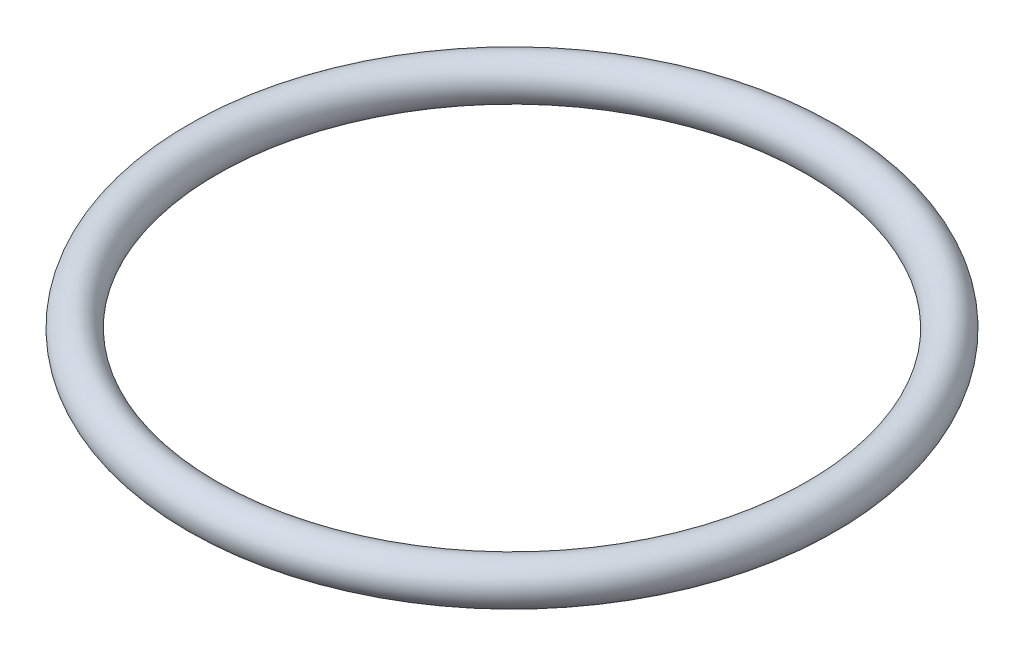
SolidWorks part; units mm, degrees
ref_plane "正面" through (0, 0, 0) normal (0, 0, 1) x (1, 0, 0)
ref_plane "平面" through (0, 0, 0) normal (0, 1, 0) x (1, 0, 0)
ref_plane "右側面" through (0, 0, 0) normal (1, 0, 0) x (0, 0, -1)
sketch "ｽｹｯﾁ1" plane through (0, 0, 0) normal (0, 0, 1) x (1, 0, 0)
  line L0 (0, 0) -> (0, 10) construction
  line L1 (0, 0) -> (30.5, 0) construction
  circle A0 centre (30.5, 0) radius 2
  dimension "D3" = 4
  dimension "D1" = 10
  dimension "D2" = 30.5
revolve "回転1" add sketch "ｽｹｯﾁ1" angle 360 about L0
